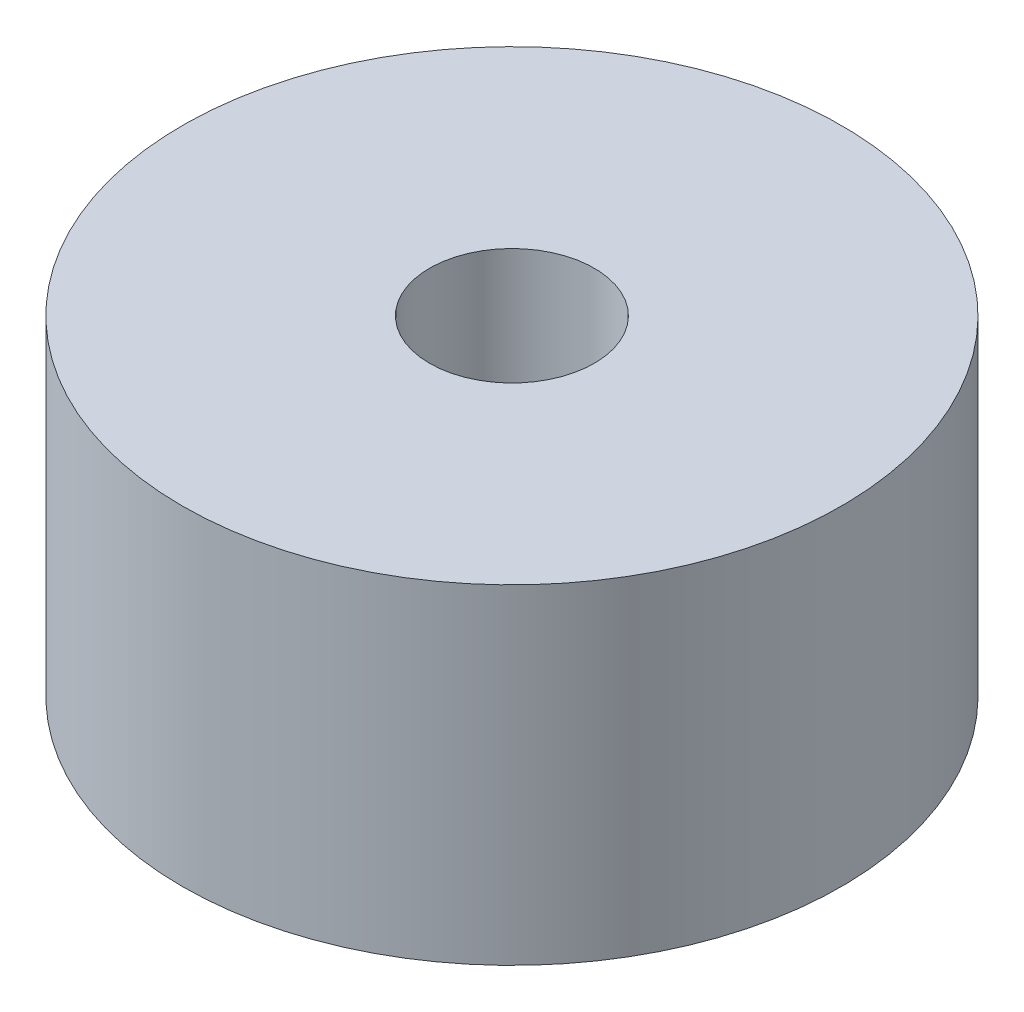
SolidWorks part; units mm, degrees
material "AISI 316 Stainless Steel Sheet (SS)"
ref_plane "Front Plane" through (0, 0, 0) normal (0, 0, 1) x (1, 0, 0)
ref_plane "Top Plane" through (0, 0, 0) normal (0, 1, 0) x (1, 0, 0)
ref_plane "Right Plane" through (0, 0, 0) normal (1, 0, 0) x (0, 0, -1)
sketch "Sketch1" plane through (0, 0, 0) normal (0, 1, 0) x (1, 0, 0)
  circle A0 centre (0, 0) radius 50.8
  dimension "D1" = 101.6
extrude "Boss-Extrude1" add sketch "Sketch1" along normal blind 50.8
sketch "Sketch3" plane through (0, 0, 0) normal (0, -1, 0) x (1, 0, 0)
  line L0 (0, 44.45) -> (0, 0) construction
  circle A1 centre (0, 44.45) radius 3.175
  dimension "D1" = 44.45
  dimension "D2" = 6.35
extrude "Cut-Extrude1" cut sketch "Sketch3" against normal blind 6.35
pattern_circular "CirPattern1" count 4 over 360 about axis through (0, 0, 0) along (0, 1, 0) of "Cut-Extrude1"
sketch "Sketch4" plane through (0, 0, 0) normal (0, -1, 0) x (1, 0, 0)
  line L0 (44.45, 3.175) -> (44.45, 5.676) construction
  line L5 (43.18, -4.7311) -> (43.18, -2.9099)
  line L7 (45.72, -4.7311) -> (45.72, -2.9099)
  line L8 (44.45, -3.1206) -> (44.45, -4.8986) construction
  arc A0 (43.18, -4.7311) -> (45.72, -4.7311) centre (44.45, 0) ccw
  arc A1 (43.18, -2.9099) -> (45.72, -2.9099) centre (44.45, 0) ccw
  circle A2 centre (44.45, 0) radius 3.175 construction
  circle A3 centre (44.45, 0) radius 3.175 construction
  point P21 (44.45, 0)
  dimension "D2" = 1.8212
  dimension "D1" = 1.778
  dimension "D3" = 2.54
extrude "Cut-Extrude2" cut sketch "Sketch4" against normal blind 6.35
sketch "Sketch5" plane through (0, 6.35, 0) normal (0, -1, 0) x (1, 0, 0)
  line L0 (47.625, 0) -> (49.3486, 0)
  line L1 (45.72, -4.7311) -> (45.72, -2.9099) construction
  line L2 (45.72, -4.7311) -> (45.72, -2.9099)
  arc A0 (45.72, -4.7311) -> (49.3486, 0) centre (44.45, 0) ccw
  arc A1 (45.72, -2.9099) -> (43.18, -2.9099) centre (44.45, 0) ccw construction
  arc A2 (45.72, -2.9099) -> (43.18, -2.9099) centre (44.45, 0) ccw construction
  arc A3 (45.72, -2.9099) -> (47.625, 0) centre (44.45, 0) ccw
extrude "Cut-Extrude3" cut sketch "Sketch5" along normal blind 2.54
pattern_circular "CirPattern2" count 4 over 360 about axis through (0, 0, 0) along (0, 1, 0) of "Cut-Extrude3", "Cut-Extrude2"
sketch "Sketch6" plane through (0, 50.8, 0) normal (0, 1, 0) x (1, 0, 0)
  circle A0 centre (0, 0) radius 12.7
extrude "Cut-Extrude4" cut sketch "Sketch6" against normal through all
